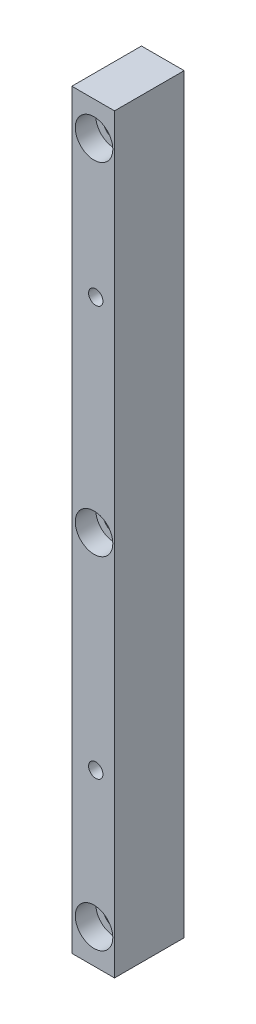
SolidWorks part; units mm, degrees
ref_plane "Plano frontal" through (0, 0, 0) normal (0, 0, 1) x (1, 0, 0)
ref_plane "Plano superior" through (0, 0, 0) normal (0, 1, 0) x (1, 0, 0)
ref_plane "Plano direito" through (0, 0, 0) normal (1, 0, 0) x (0, 0, -1)
sketch "Esboço1" plane through (0, 0, 0) normal (0, 0, 1) x (1, 0, 0)
  line L1 (-117, -110) -> (-104.5, -110)
  line L2 (-117, -110) -> (-117, 110)
  line L3 (-117, 110) -> (-104.5, 110)
  line L4 (-104.5, -110) -> (-104.5, 110)
extrude "Ressalto-extrusão1" add sketch "Esboço1" along normal up to vertex (20.4 mm away)
hole_wizard "Rebaixo para SHCS M61" positions "Esboço2" profile "Esboço3" counterbore size "M6" standard "Ansi Metric" end condition through all
sketch "Esboço2" plane through (0, 0, 20.4) normal (0, 0, 1) x (1, 0, 0)
  point P0 (-110.5, 100)
  point P3 (-110.5, 0)
  point P6 (-110.5, -100)
sketch "Esboço3" plane through (-110.5, 100, 20.4) normal (1, 0, 0) x (0, -1, 0)
  line L0 (0, 0) -> (0, 20.4)
  line L1 (0, 20.4) -> (3.3, 20.4)
  line L3 (3.3, 20.4) -> (3.3, 6)
  line L4 (3.3, 6) -> (5.5, 6)
  line L5 (5.5, 6) -> (5.5, 0)
  line L7 (5.5, 0) -> (0, 0)
  line L11 (0, -6.35) -> (0, 107.95) construction
  dimension "Thru Hole Dia." = 6.6
  dimension "Thru Hole Depth" = 20.4
  dimension "C'Bore Dia." = 11
  dimension "C'Bore Depth" = 6
hole_wizard "Furo roscado de M5x0.81" positions "Esboço4" profile "Esboço5" tap size "M5x0.8" standard "Ansi Metric" end condition through all
sketch "Esboço4" plane through (0, 0, 20.4) normal (0, 0, 1) x (1, 0, 0)
  point P0 (-110, 60)
  point P3 (-110, -60)
sketch "Esboço5" plane through (-110, 60, 20.4) normal (1, 0, 0) x (0, -1, 0)
  line L0 (0, 0) -> (0, 20.4)
  line L1 (0, 20.4) -> (2.1, 20.4)
  line L2 (2.1, 20.4) -> (2.1, 0)
  line L5 (2.1, 0) -> (0, 0)
  line L11 (0, -6.35) -> (0, 107.95) construction
  dimension "Thru Tap Drill Dia." = 4.2
  dimension "Thru Tap Drill Depth" = 20.4
cosmetic thread "Rosca de furo1"
cosmetic thread "Rosca de furo2"
